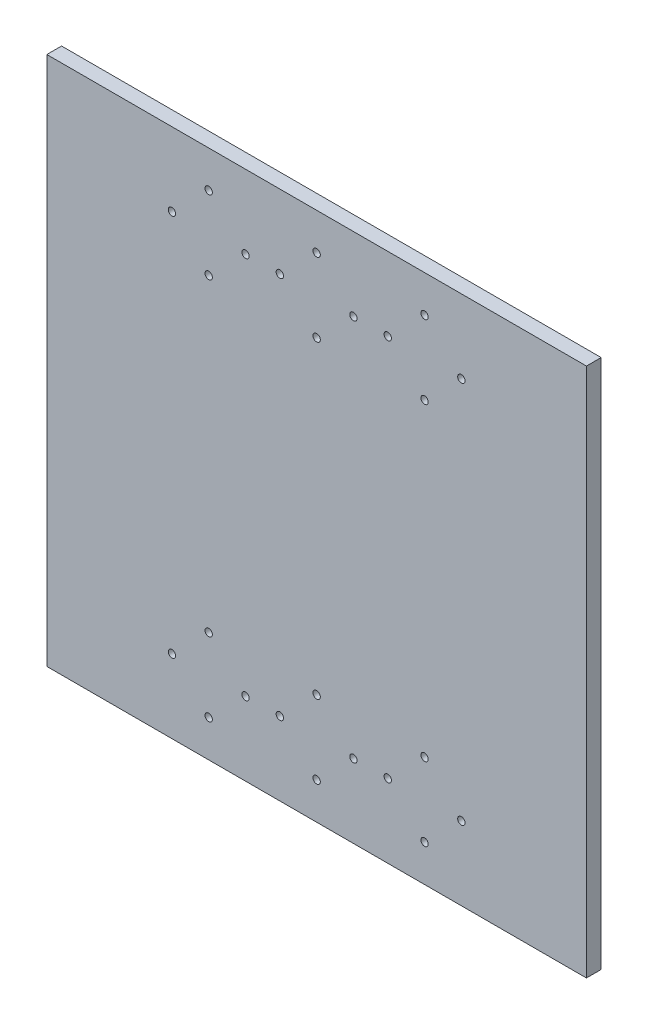
SolidWorks part; units mm, degrees
ref_plane "Alzado" through (0, 0, 0) normal (0, 0, 1) x (1, 0, 0)
ref_plane "Planta" through (0, 0, 0) normal (0, 1, 0) x (1, 0, 0)
ref_plane "Vista lateral" through (0, 0, 0) normal (1, 0, 0) x (0, 0, -1)
sketch "Croquis1" plane through (0, 0, 0) normal (0, 0, 1) x (1, 0, 0)
  line L1 (-55, -54.02) -> (55, -54.02)
  line L2 (-55, -54.02) -> (-55, 54.02)
  line L3 (-55, 54.02) -> (55, 54.02)
  line L4 (55, -54.02) -> (55, 54.02)
  line L5 (-55, -54.02) -> (55, 54.02) construction
  line L6 (-55, 54.02) -> (55, -54.02) construction
  point P0 (0, 0)
  dimension "D1" = 108.04
  dimension "D2" = 110
extrude "Saliente-Extruir1" add sketch "Croquis1" along normal blind 3
sketch "Croquis2" plane through (0, 0, 3) normal (0, 0, 1) x (1, 0, 0)
  line L0 (-55, -39.02) -> (55, -39.02) construction
  line L1 (-55, 54.02) -> (-55, -54.02) construction
  line L2 (55, -54.02) -> (55, 54.02) construction
  line L3 (-55, -31.52) -> (55, -31.52) construction
  line L4 (0, -54.02) -> (0, 54.02) construction
  line L5 (-55, -54.02) -> (55, -54.02) construction
  line L6 (55, 54.02) -> (-55, 54.02) construction
  line L7 (-55, -46.52) -> (55, -46.52) construction
  line L8 (-55, 0) -> (55, 0) construction
  circle A0 centre (7.5, -39.02) radius 0.75
  circle A1 centre (-7.5, -39.02) radius 0.75
  circle A2 centre (0, -46.52) radius 0.75
  circle A3 centre (0, -31.52) radius 0.75
  circle A4 centre (14.5, -39.02) radius 0.75
  circle A5 centre (22, -31.52) radius 0.75
  circle A6 centre (22, -46.52) radius 0.75
  circle A7 centre (29.5, -39.02) radius 0.75
  circle A8 centre (-22, -31.52) radius 0.75
  circle A9 centre (-29.5, -39.02) radius 0.75
  circle A10 centre (-22, -46.52) radius 0.75
  circle A11 centre (-14.5, -39.02) radius 0.75
  circle A12 centre (29.5, 39.02) radius 0.75
  circle A13 centre (22, 31.52) radius 0.75
  circle A14 centre (22, 46.52) radius 0.75
  circle A15 centre (14.5, 39.02) radius 0.75
  circle A16 centre (7.5, 39.02) radius 0.75
  circle A17 centre (0, 46.52) radius 0.75
  circle A18 centre (0, 31.52) radius 0.75
  circle A19 centre (-7.5, 39.02) radius 0.75
  circle A20 centre (-14.5, 39.02) radius 0.75
  circle A21 centre (-22, 46.52) radius 0.75
  circle A22 centre (-22, 31.52) radius 0.75
  circle A23 centre (-29.5, 39.02) radius 0.75
  point P6 (0, -39.02)
  dimension "D1" = 15
  dimension "D2" = 1.5
  dimension "D3" = 15
  dimension "D4" = 7.5
  dimension "D5" = 7.5
  dimension "D6" = 7
  dimension "D7" = 15
  dimension "D8" = 7.5
  dimension "D9" = 7.5
extrude "Cortar-Extruir1" cut sketch "Croquis2" against normal up to next
